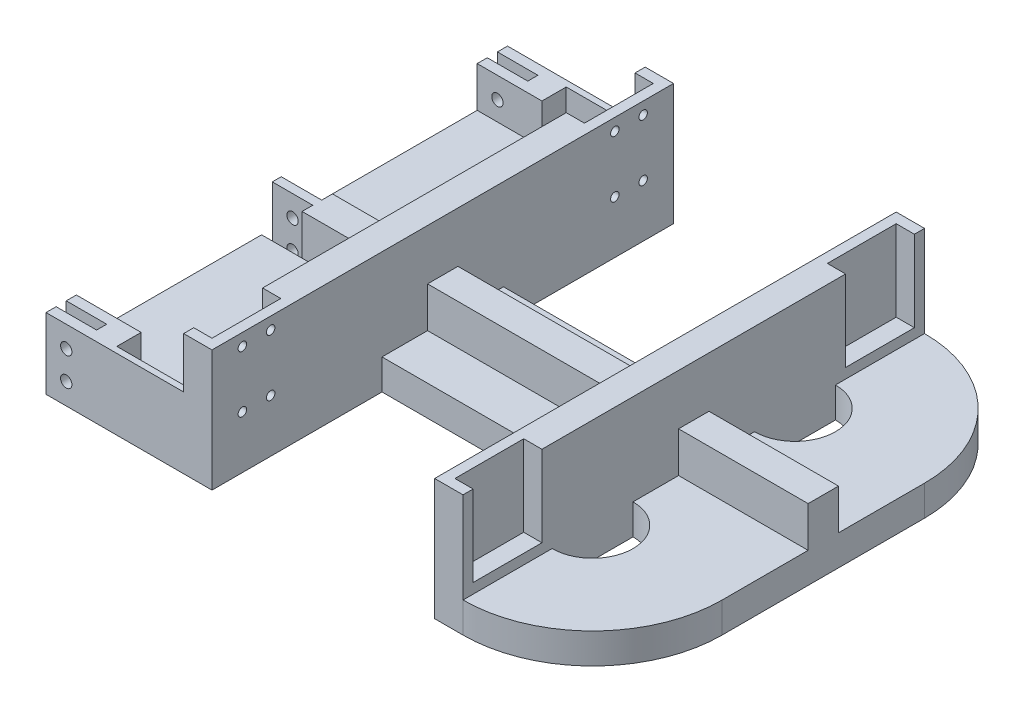
SolidWorks part; units mm, degrees
ref_plane "Front Plane" through (0, 0, 0) normal (0, 0, 1) x (1, 0, 0)
ref_plane "Top Plane" through (0, 0, 0) normal (0, 1, 0) x (1, 0, 0)
ref_plane "Right Plane" through (0, 0, 0) normal (1, 0, 0) x (0, 0, -1)
sketch "Sketch2" plane through (0, 0, 0) normal (0, 1, 0) x (1, 0, 0)
  line L0 (62.5, 25) -> (62.5, -25)
  line L1 (23.5, -35) -> (30.5, -35)
  line L2 (23.5, -57) -> (30.5, -57)
  line L3 (30.5, -15) -> (-38.5, -15)
  line L4 (-62.5, 0) -> (62.5, 0) construction
  line L5 (30.5, 57) -> (30.5, -57) construction
  line L6 (23.5, -35) -> (23.5, -57)
  line L7 (-31.5, -35) -> (-38.5, -35)
  line L8 (-31.5, -57) -> (-38.5, -57)
  line L9 (-38.5, -57) -> (-38.5, 57) construction
  line L10 (62.5, -25) -> (-62.5, -25) construction
  line L11 (-38.5, -57) -> (-62.5, -57)
  line L12 (-31.5, -35) -> (-31.5, -57)
  line L13 (-62.5, -57) -> (-62.5, 57)
  line L14 (62.5, 25) -> (-62.5, 25) construction
  line L15 (-31.5, 35) -> (-31.5, 57)
  line L16 (-38.5, 57) -> (-62.5, 57)
  line L17 (-31.5, 57) -> (-38.5, 57)
  line L18 (-31.5, 35) -> (-38.5, 35)
  line L19 (23.5, 35) -> (23.5, 57)
  line L20 (30.5, 15) -> (-38.5, 15)
  line L21 (23.5, 57) -> (30.5, 57)
  line L22 (23.5, 35) -> (30.5, 35)
  arc A0 (62.5, -25) -> (30.5, -57) centre (30.5, -25) cw
  arc A1 (30.5, -35) -> (30.5, -15) centre (30.5, -25) ccw
  arc A2 (-38.5, -15) -> (-38.5, -35) centre (-38.5, -25) ccw
  arc A3 (-38.5, 15) -> (-38.5, 35) centre (-38.5, 25) cw
  arc A4 (30.5, 35) -> (30.5, 15) centre (30.5, 25) cw
  arc A5 (62.5, 25) -> (30.5, 57) centre (30.5, 25) ccw
  point P33 (-38.5, 0)
  point P34 (30.5, 0)
  point P45 (0, 0)
  dimension "D2" = 10
  dimension "D1" = 25
  dimension "D3" = 125
  dimension "D4" = 55
  dimension "D5" = 22
  dimension "D6" = 7
extrude "Boss-Extrude1" add sketch "Sketch2" along normal blind 2.5 and the other way blind 5
sketch "Sketch3" plane through (0, 2.5, 0) normal (0, 1, 0) x (1, 0, 0)
  line L13 (-38.5, -35) -> (-31.5, -35)
  line L14 (-31.5, -35) -> (-31.5, -57)
  line L15 (-31.5, -57) -> (-38.5, -57)
  line L16 (-62.5, -57) -> (-31.5, -57) construction
  line L19 (30.5, -35) -> (23.5, -35)
  line L20 (23.5, -35) -> (23.5, -57)
  line L21 (23.5, -57) -> (30.5, -57)
  line L26 (23.5, 57) -> (30.5, 57)
  line L27 (23.5, 35) -> (23.5, 57)
  line L28 (30.5, 35) -> (23.5, 35)
  line L31 (-31.5, 57) -> (-38.5, 57)
  line L32 (-31.5, 35) -> (-31.5, 57)
  line L33 (-38.5, 35) -> (-31.5, 35)
  line L45 (-38.5, -35) -> (-38.5, -57)
  line L46 (30.5, -35) -> (30.5, -57)
  line L47 (-38.5, 57) -> (-38.5, 35)
  line L48 (30.5, 57) -> (30.5, 35)
extrude "Boss-Extrude4" add sketch "Sketch3" along normal blind 2.5 contours L47 L33 L32 L31 | L48 L28 L27 L26 | L46 L21 L20 L19 | L45 L15 L14 L13
sketch "Sketch6" plane through (0, 5, 0) normal (0, 1, 0) x (1, 0, 0)
  line L0 (-38.5, -35) -> (-31.5, -35)
  line L1 (-31.5, -35) -> (-31.5, -57)
  line L2 (-31.5, -57) -> (-38.5, -57)
  line L3 (-38.5, -57) -> (-38.5, -54.5)
  line L4 (-38.5, -35) -> (-38.5, -57) construction
  line L5 (-38.5, -54.5) -> (-34, -54.5)
  line L6 (-34, -54.5) -> (-34, -37.5)
  line L7 (-34, -37.5) -> (-38.5, -37.5)
  line L8 (30.5, -35) -> (30.5, -57) construction
  line L9 (-38.5, -37.5) -> (-38.5, -35)
  line L10 (-84.6666, 0) -> (76.6431, 0) construction
  line L11 (30.5, -35) -> (23.5, -35)
  line L12 (23.5, -35) -> (23.5, -57)
  line L13 (23.5, -57) -> (30.5, -57)
  line L14 (30.5, -57) -> (30.5, -54.5)
  line L15 (30.5, 37.5) -> (30.5, 35)
  line L16 (30.5, -54.5) -> (26, -54.5)
  line L17 (26, -54.5) -> (26, -37.5)
  line L18 (26, -37.5) -> (30.5, -37.5)
  line L19 (26, 37.5) -> (30.5, 37.5)
  line L20 (30.5, -37.5) -> (30.5, -35)
  line L38 (26, 54.5) -> (26, 37.5)
  line L39 (30.5, 54.5) -> (26, 54.5)
  line L40 (30.5, 57) -> (30.5, 54.5)
  line L41 (23.5, 57) -> (30.5, 57)
  line L42 (23.5, 35) -> (23.5, 57)
  line L43 (30.5, 35) -> (23.5, 35)
  line L44 (-38.5, 37.5) -> (-38.5, 35)
  line L45 (-34, 37.5) -> (-38.5, 37.5)
  line L46 (-34, 54.5) -> (-34, 37.5)
  line L47 (-38.5, 54.5) -> (-34, 54.5)
  line L48 (-38.5, 57) -> (-38.5, 54.5)
  line L49 (-31.5, 57) -> (-38.5, 57)
  line L50 (-31.5, 35) -> (-31.5, 57)
  line L51 (-38.5, 35) -> (-31.5, 35)
  point P22 (30.5, -36.25)
  dimension "D1" = 4.5
  dimension "D2" = 2.5
  dimension "D3" = 7
  dimension "D4" = 22
  dimension "D5" = 7
  dimension "D6" = 2.5
  dimension "D7" = 22
  dimension "D8" = 4.5
extrude "Boss-Extrude5" add sketch "Sketch6" along normal blind 20
sketch "Sketch7" plane through (23.5, 0, 0) normal (-1, 0, 0) x (0, 0, 1)
  line L0 (37.5, 25) -> (54.5, 25) construction
  line L1 (35, 25) -> (57, 25) construction
  line L4 (0, 2.5) -> (0, 37.0796) construction
  line L5 (-57, 2.5) -> (57, 2.5) construction
  circle A0 centre (46, 13.75) radius 3.75
  circle A1 centre (-46, 13.75) radius 3.75
  point P4 (46, 25)
  dimension "D1" = 7.5
  dimension "D2" = 11.25
extrude "Boss-Extrude6" add sketch "Sketch7" along normal blind 5.5 contours A0 | A1
sketch "Sketch10" plane through (-31.5, 0, 0) normal (1, 0, 0) x (0, 0, -1)
  line L0 (46, 25) -> (46, -5) construction
  line L3 (-46, 25) -> (-46, -5) construction
  line L4 (-57, 25) -> (-35, 25) construction
  line L5 (-57, -5) -> (-35, -5) construction
  line L7 (0, 2.5) -> (0, 43.5251) construction
  line L8 (-25, 2.5) -> (25, 2.5) construction
  circle A0 centre (-42.5, 22) radius 1.05
  circle A1 centre (-49.5, 22) radius 1.05
  circle A4 centre (-49.5, 8) radius 1.05
  circle A5 centre (-42.5, 8) radius 1.05
  circle A6 centre (42.5, 8) radius 1.05
  circle A7 centre (49.5, 8) radius 1.05
  circle A8 centre (49.5, 22) radius 1.05
  circle A9 centre (42.5, 22) radius 1.05
  dimension "D3" = 2.1
  dimension "D1" = 3
  dimension "D2" = 3.5
  dimension "D4" = 14
  dimension "D5" = 3.5
extrude "Cut-Extrude1" cut sketch "Sketch10" against normal blind 2.5
sketch "Sketch14" plane through (0, 2.5, 0) normal (0, 1, 0) x (1, 0, 0)
  line L0 (-62.5, 57) -> (-62.5, -57) construction
  line L1 (-62.5, 3.75) -> (62.5, 3.75)
  line L2 (-62.5, 3.75) -> (-62.5, -3.75)
  line L3 (-62.5, -3.75) -> (62.5, -3.75)
  line L4 (62.5, 3.75) -> (62.5, -3.75)
  line L5 (62.5, -25) -> (62.5, 25) construction
  line L6 (-62.5, -57) -> (-56.5, -57)
  line L7 (-62.5, -57) -> (-62.5, -49.5)
  line L8 (-62.5, -49.5) -> (-56.5, -49.5)
  line L9 (-56.5, -57) -> (-56.5, -49.5)
  line L10 (-62.5, 57) -> (-56.5, 57)
  line L11 (-62.5, 57) -> (-62.5, 49.5)
  line L12 (-62.5, 49.5) -> (-56.5, 49.5)
  line L13 (-56.5, 57) -> (-56.5, 49.5)
  line L14 (-38.5, -35) -> (-38.5, -57) construction
  line L15 (-56.5, -57) -> (-38.5, -57)
  line L16 (-56.5, -57) -> (-56.5, -55.5)
  line L17 (-56.5, -55.5) -> (-38.5, -55.5)
  line L18 (-38.5, -57) -> (-38.5, -55.5)
  line L19 (-38.5, 57) -> (-38.5, 35) construction
  line L20 (-56.5, 57) -> (-38.5, 57)
  line L21 (-56.5, 57) -> (-56.5, 55.5)
  line L22 (-56.5, 55.5) -> (-38.5, 55.5)
  line L23 (-38.5, 57) -> (-38.5, 55.5)
  point P6 (62.5, 0)
  line M14 (-38.5, 57) -> (-62.5, 57)
  line M15 (-62.5, 57) -> (-62.5, -57)
  line M16 (-62.5, -57) -> (-38.5, -57)
  line M23 (62.5, -25) -> (62.5, 25)
  line M33 (-38.5, 35) -> (-38.5, 57)
  line M40 (-38.5, -57) -> (-38.5, -35)
  dimension "D1" = 7.5
  dimension "D2" = 6
  dimension "D3" = 7.5
  dimension "D4" = 1.5
extrude "Boss-Extrude8" add sketch "Sketch14" along normal blind 10 contours L3 L1 M15 M23 | L9 L8 M16 M15 | L17 L9 M16 M40 | L13 L12 M14 M15 | L13 L22 M33 M14
sketch "Sketch15" plane through (-62.5, 0, 0) normal (-1, 0, 0) x (0, 0, 1)
  line L0 (-57, -5) -> (57, -5) construction
  line L5 (-1.1, 12.5) -> (1.1, 12.5)
  line L6 (57, 12.5) -> (54.5, 12.5)
  line L7 (57, 12.5) -> (57, -5)
  line L8 (57, -5) -> (54.5, -5)
  line L9 (54.5, 12.5) -> (54.5, -5)
  line L10 (49.5, 12.5) -> (52, 12.5)
  line L11 (49.5, 12.5) -> (49.5, -5)
  line L12 (49.5, -5) -> (52, -5)
  line L13 (52, 12.5) -> (52, -5)
  line L14 (57, -5) -> (57, 12.5) construction
  line L27 (-3.75, 12.5) -> (3.75, 12.5) construction
  line L28 (1.1, 12.5) -> (1.1, -5)
  line L29 (1.1, -5) -> (-1.1, -5)
  line L31 (0, 12.5) -> (0, -5) construction
  line L32 (-1.1, 12.5) -> (-1.1, -5)
  line L33 (-52, 12.5) -> (-52, -5)
  line L34 (-49.5, -5) -> (-52, -5)
  line L35 (-49.5, 12.5) -> (-49.5, -5)
  line L36 (-49.5, 12.5) -> (-52, 12.5)
  line L37 (-54.5, 12.5) -> (-54.5, -5)
  line L38 (-57, -5) -> (-54.5, -5)
  line L39 (-57, 12.5) -> (-57, -5)
  line L40 (-57, 12.5) -> (-54.5, 12.5)
  line L41 (49.5, 12.5) -> (57, 12.5) construction
  line L42 (49.5, 12.5) -> (49.5, 2.5) construction
  point P11 (0, 12.5)
  point P31 (0, -5)
  dimension "D1" = 2.2
  dimension "D2" = 2.5
extrude "Boss-Extrude9" add sketch "Sketch15" along normal blind 10
sketch "Sketch16" plane through (0, 0, 57) normal (0, 0, 1) x (1, 0, 0)
  line L0 (-72.5, -5) -> (-72.5, 12.5) construction
  line L2 (-72.5, -5) -> (-72.5, 12.5) construction
  line L4 (-72.5, 3.75) -> (-31.5, 3.75) construction
  line L7 (-31.5, -5) -> (-31.5, 25) construction
  circle A2 centre (-67.5, 7.25) radius 1.4
  circle A3 centre (-67.5, 0.25) radius 1.4
  dimension "D1" = 2.8
  dimension "D2" = 5
  dimension "D3" = 3.5
extrude "Cut-Extrude3" cut sketch "Sketch16" against normal blind 114
sketch "Sketch17" plane through (0, 0, -35) normal (0, 0, 1) x (1, 0, 0)
  line L0 (-38.5, 25) -> (-31.5, 25) construction
  line L1 (-38.5, 25) -> (-31.5, 25)
  line L2 (-38.5, 25) -> (-38.5, -5)
  line L3 (-38.5, -5) -> (-31.5, -5)
  line L4 (-31.5, 25) -> (-31.5, -5)
  line L5 (23.5, 25) -> (30.5, 25)
  line L6 (23.5, 25) -> (23.5, -5)
  line L7 (23.5, -5) -> (30.5, -5)
  line L8 (30.5, 25) -> (30.5, -5)
  line L9 (23.5, 25) -> (30.5, 25) construction
  dimension "D1" = 7
  dimension "D2" = 7
extrude "Boss-Extrude10" add sketch "Sketch17" along normal blind 70
sketch "Sketch18" plane through (-62.5, 0, 0) normal (-1, 0, 0) x (0, 0, 1)
  line L0 (3.75, 12.5) -> (3.75, 2.5) construction
  line L1 (-49.5, 2.5) -> (-3.75, 2.5)
  line L2 (-49.5, 2.5) -> (-49.5, -5)
  line L3 (-49.5, -5) -> (-3.75, -5)
  line L4 (-3.75, 2.5) -> (-3.75, -5)
  line L5 (3.75, -5) -> (49.5, -5)
  line L6 (3.75, -5) -> (3.75, 2.5)
  line L7 (3.75, 2.5) -> (49.5, 2.5)
  line L8 (49.5, -5) -> (49.5, 2.5)
  line L9 (-3.75, 12.5) -> (-3.75, 2.5) construction
extrude "Boss-Extrude11" add sketch "Sketch18" along normal blind 10
